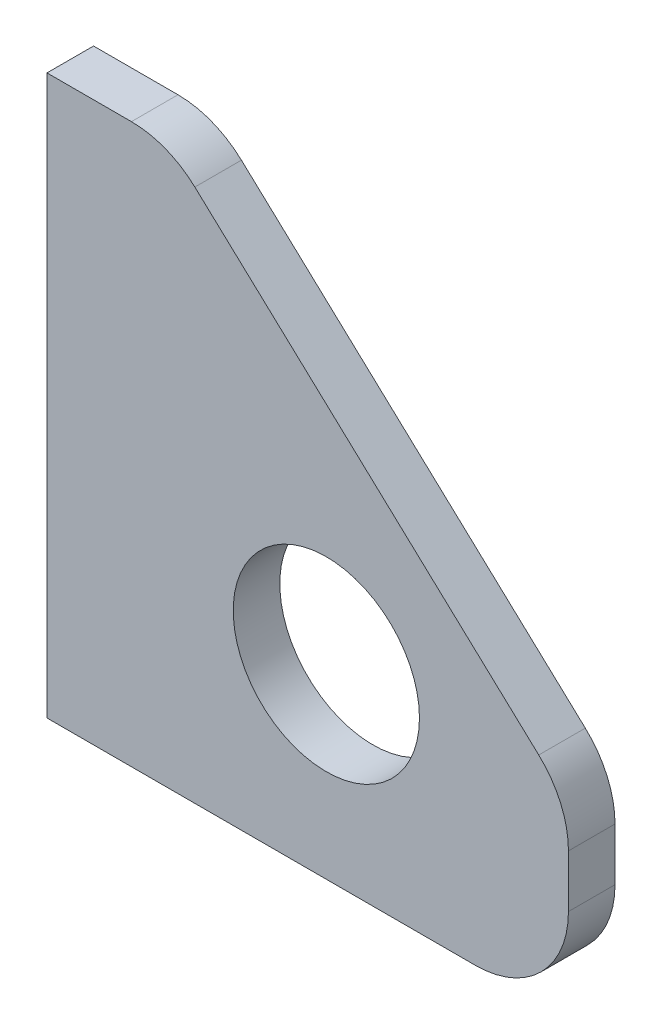
SolidWorks part; units mm, degrees
ref_plane "Front Plane" through (0, 0, 0) normal (0, 0, 1) x (1, 0, 0)
ref_plane "Top Plane" through (0, 0, 0) normal (0, 1, 0) x (1, 0, 0)
ref_plane "Right Plane" through (0, 0, 0) normal (1, 0, 0) x (0, 0, -1)
sketch "Sketch1" plane through (0, 0, 0) normal (0, 0, 1) x (1, 0, 0)
  line L0 (0, 0) -> (0, -20) construction
  line L1 (0, -20) -> (-30, -20)
  line L2 (-30, -20) -> (-30, 40)
  line L3 (-30, 40) -> (-17, 40)
  line L4 (-17, 40) -> (26, 0)
  line L5 (26, 0) -> (26, -20)
  line L6 (26, -20) -> (0, -20)
  line L7 (0, 0) -> (-30, 0) construction
  circle A0 centre (0, 0) radius 10
  dimension "D2" = 20
  dimension "D1" = 60
  dimension "D3" = 20
  dimension "D4" = 20
  dimension "D5" = 13
  dimension "D6" = 30
  dimension "D7" = 26
extrude "Boss-Extrude1" add sketch "Sketch1" along normal blind 5
fillet "Fillet1" radius 10 3 edges at (26, -20, 2.5) (26, 0, 2.5) (-17, 40, 2.5)
